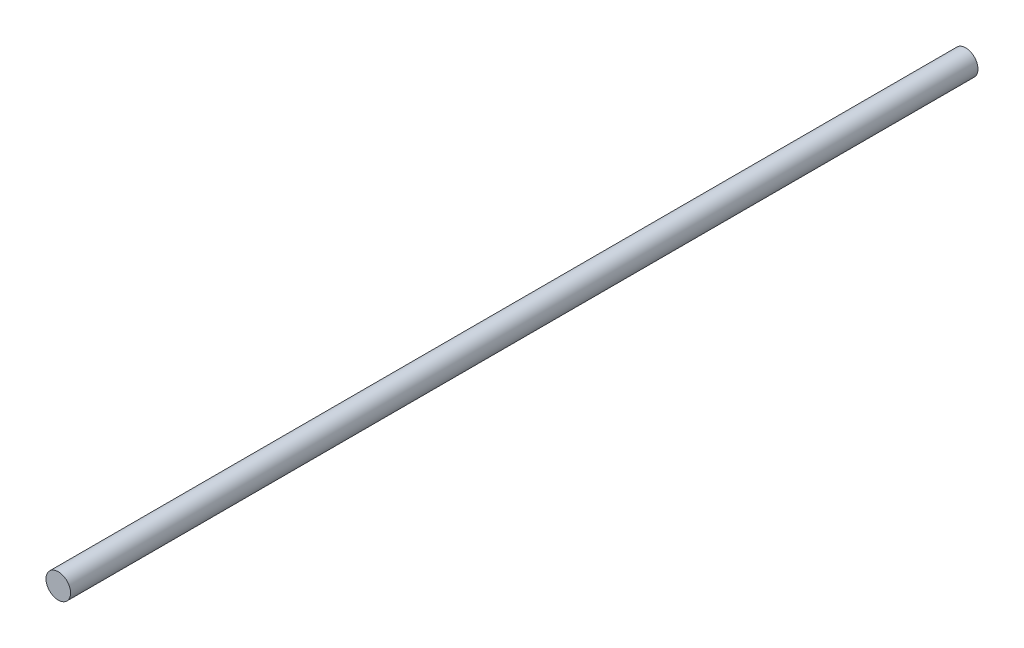
SolidWorks part; units mm, degrees
ref_plane "Plan de face" through (0, 0, 0) normal (0, 0, 1) x (1, 0, 0)
ref_plane "Plan de dessus" through (0, 0, 0) normal (0, 1, 0) x (1, 0, 0)
ref_plane "Plan de droite" through (0, 0, 0) normal (1, 0, 0) x (0, 0, -1)
sketch "Esquisse1" plane through (0, 0, 0) normal (0, 0, 1) x (1, 0, 0)
  circle A0 centre (0, 0) radius 4
  dimension "D1" = 8
extrude "Boss.-Extru.1" add sketch "Esquisse1" along normal blind 295
